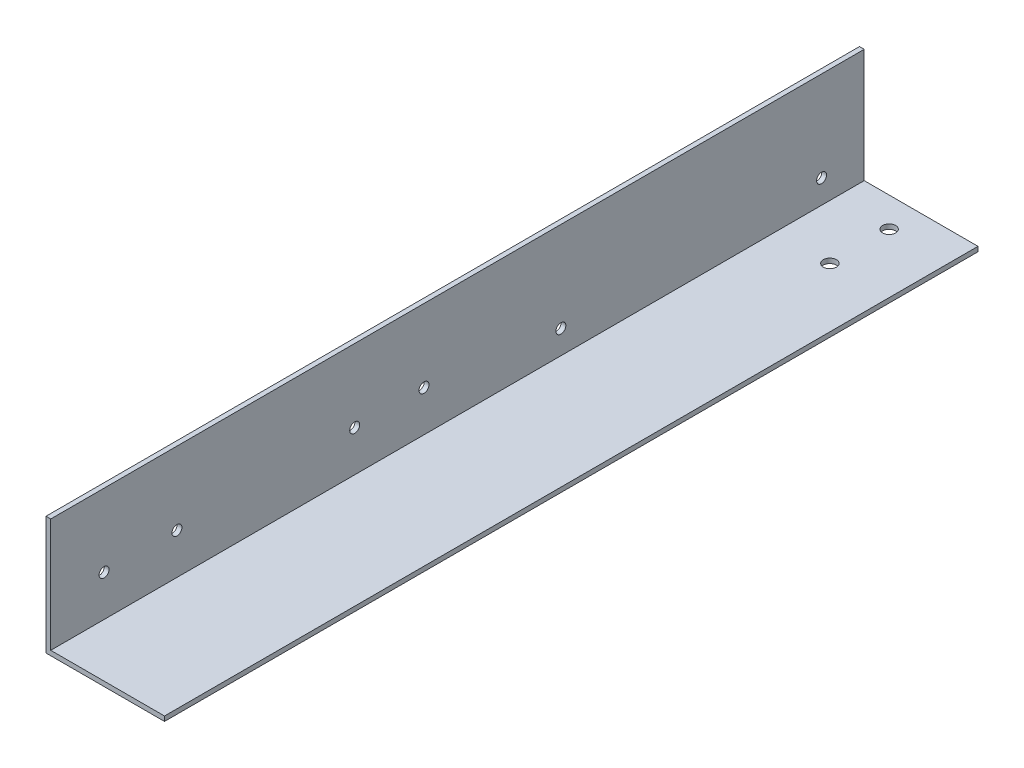
SolidWorks part; units mm, degrees
ref_plane "Front Plane" through (0, 0, 0) normal (0, 0, 1) x (1, 0, 0)
ref_plane "Top Plane" through (0, 0, 0) normal (0, 1, 0) x (1, 0, 0)
ref_plane "Right Plane" through (0, 0, 0) normal (1, 0, 0) x (0, 0, -1)
sketch "Sketch1" plane through (0, 0, 0) normal (0, 0, 1) x (1, 0, 0)
  line L0 (0, 0) -> (50, 0)
  line L1 (50, 0) -> (50, 2)
  line L2 (50, 2) -> (2, 2)
  line L3 (2, 2) -> (2, 50)
  line L4 (2, 50) -> (0, 50)
  line L5 (0, 50) -> (0, 0)
  dimension "D1" = 50
  dimension "D2" = 50
  dimension "D3" = 2
  dimension "D4" = 2
extrude "Boss-Extrude1" add sketch "Sketch1" along normal blind 343.25
sketch "Sketch2" plane through (0, 0, 0) normal (1, 0, 0) x (0, 0, -1)
  circle A0 centre (-185.75, 19.25) radius 2.1
  circle A1 centre (-215, 19.25) radius 2.1
  circle A2 centre (-290, 19.25) radius 2.1
  circle A3 centre (-320.75, 19.25) radius 2.1
  dimension "D1" = 4.2
  dimension "D2" = 19.25
  dimension "D3" = 185.75
  dimension "D4" = 215
  dimension "D5" = 290
  dimension "D6" = 320.75
extrude "Cut-Extrude1" cut sketch "Sketch2" against normal mid plane 10
sketch "Sketch3" plane through (0, 0, 0) normal (1, 0, 0) x (0, 0, -1)
  circle A0 centre (-18, 12) radius 2.1
  circle A1 centre (-128, 12) radius 2.1
  dimension "D1" = 4.2
  dimension "D2" = 12
  dimension "D3" = 18
  dimension "D4" = 128
extrude "Cut-Extrude2" cut sketch "Sketch3" against normal mid plane 10
sketch "Sketch4" plane through (0, 0, 0) normal (0, 1, 0) x (1, 0, 0)
  circle A0 centre (25, -12.5) radius 2.75
  circle A1 centre (25, -37.5) radius 2.75
  dimension "D1" = 5.5
  dimension "D2" = 25
  dimension "D3" = 12.5
  dimension "D4" = 37.5
extrude "Cut-Extrude3" cut sketch "Sketch4" against normal mid plane 10
